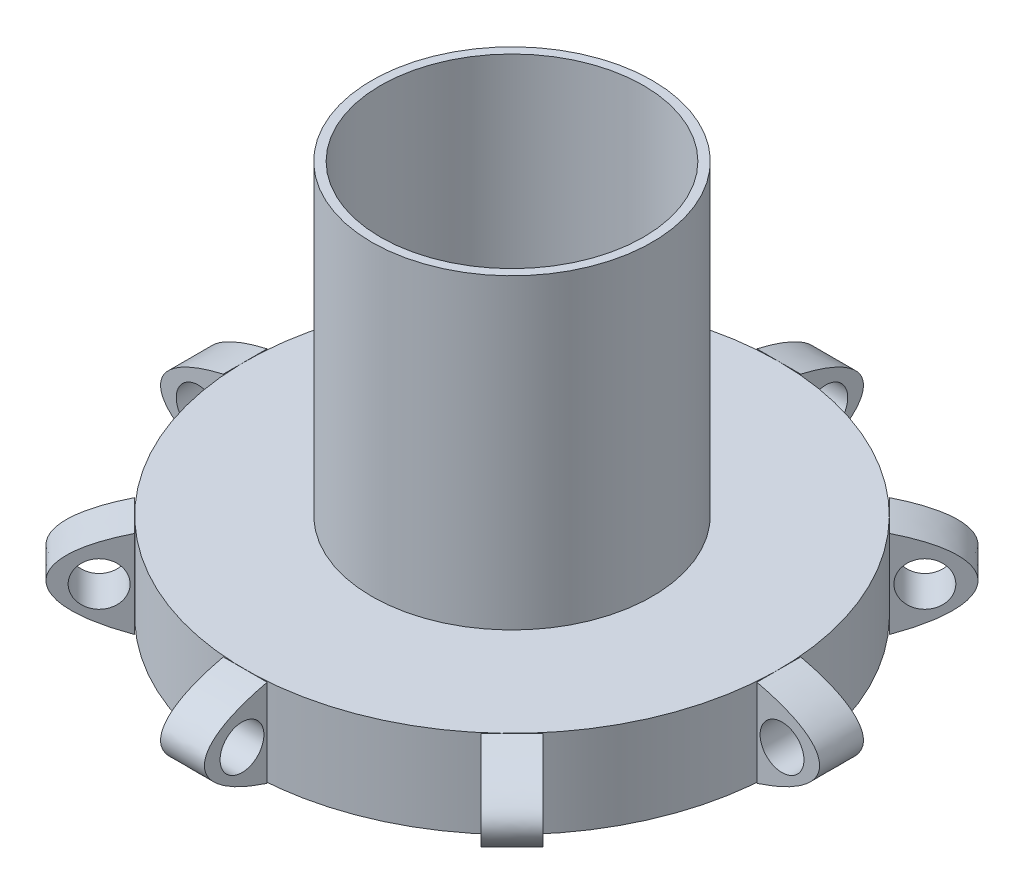
SolidWorks part; units mm, degrees
ref_plane "Front Plane" through (0, 0, 0) normal (0, 0, 1) x (1, 0, 0)
ref_plane "Top Plane" through (0, 0, 0) normal (0, 1, 0) x (1, 0, 0)
ref_plane "Right Plane" through (0, 0, 0) normal (1, 0, 0) x (0, 0, -1)
sketch "Sketch1" plane through (0, 0, 0) normal (0, 0, 1) x (1, 0, 0)
  line L0 (0, 0) -> (0, 23.8934)
  line L1 (0, 23.8934) -> (16, 23.8934)
  line L7 (16, -26.1066) -> (0, -26.1066)
  line L8 (0, 0) -> (0, -26.1066)
  line L9 (16, 23.8934) -> (16, -11.1066)
  line L10 (16, -11.1066) -> (30.4416, -11.1066)
  line L11 (30.4416, -11.1066) -> (30.4416, -21.1066)
  line L12 (30.4416, -21.1066) -> (16, -21.1066)
  line L13 (16, -21.1066) -> (17.8355, -24.6462)
  line L14 (16.9478, -26.1066) -> (16, -26.1066)
  arc A0 (17.8355, -24.6462) -> (16.9478, -26.1066) centre (16.9478, -25.1066) cw
  dimension "D6" = 1
  dimension "D1" = 16
  dimension "D2" = 16
  dimension "D4" = 3.5397
  dimension "D5" = 45
revolve "Revolve1" add sketch "Sketch1" angle 360 about L0
sketch "Sketch2" plane through (0, 23.8934, 0) normal (0, 1, 0) x (1, 0, 0)
  circle A0 centre (0, 0) radius 15
  dimension "D1" = 30
extrude "Cut-Extrude1" cut sketch "Sketch2" against normal up to surface (50 mm away) up to face at (0, -26.1066, -16.9478)
ref_plane "Plane1" through (30.4416, 0, 0) normal (1, 0, 0) x (0, 0, -1)
sketch "Sketch3" plane through (30.4416, 0, 0) normal (1, 0, 0) x (0, 0, -1)
  line L0 (0, -11.1066) -> (0, -21.1066)
  line L1 (30.4416, -11.1066) -> (-30.4416, -11.1066) construction
  line L2 (-16, -21.1066) -> (16, -21.1066) construction
ref_plane "Plane2" through (0, 0, 0) normal (0, 0, 1) x (0, -1, 0)
sketch "Sketch4" plane through (0, 0, 0) normal (0, 0, 1) x (0, -1, 0)
  line L0 (11.1066, 30.4416) -> (21.1066, 30.4416) construction
  line L1 (5.5, 30.4416) -> (-5.5, 30.4416) construction
  line L2 (11.1066, 30.4416) -> (21.1066, 30.4416)
  spline S0 degree 3 poles (11.1066, 30.4416) (13.2797, 39.8642) (17.9629, 40.0986) (21.1066, 30.4416) knots 0 0 0 0 1 1 1 1
extrude "Boss-Extrude1" add sketch "Sketch4" along normal mid plane 5 separate body
sketch "Sketch5" plane through (0, 0, -2.5) normal (0, 0, -1) x (-1, 0, 0)
  line L0 (30.4416, -11.1066) -> (-30.4416, -11.1066) construction
  circle A0 centre (-33.3091, -16.1066) radius 2.5
  dimension "D2" = 5
  dimension "D1" = 5
extrude "Cut-Extrude2" cut sketch "Sketch5" against normal through all
pattern_circular "CirPattern1" count 8 over 360 about axis through (0, -11.1066, 0) along (0, -1, 0) of bodies 104
